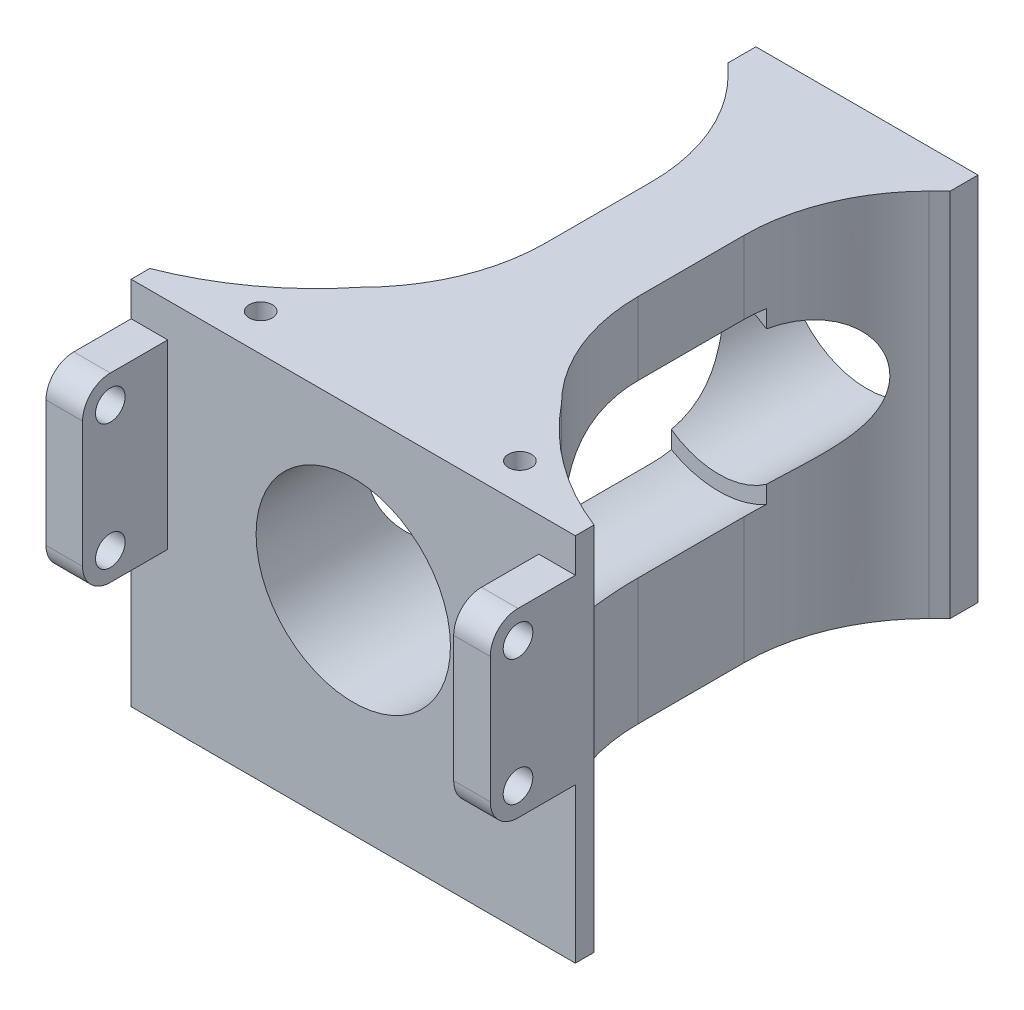
SolidWorks part; units mm, degrees
material "6061 合金"
ref_plane "前视基准面" through (0, 0, 0) normal (0, 0, 1) x (1, 0, 0)
ref_plane "上视基准面" through (0, 0, 0) normal (0, 1, 0) x (1, 0, 0)
ref_plane "右视基准面" through (0, 0, 0) normal (1, 0, 0) x (0, 0, -1)
sketch "草图1" plane through (0, 0, 0) normal (0, 0, 1) x (1, 0, 0)
  line L1 (-24, -15.5) -> (24, -15.5)
  line L2 (-24, -15.5) -> (-24, 15.5)
  line L3 (-24, 15.5) -> (24, 15.5)
  line L4 (24, -15.5) -> (24, 15.5)
  line L5 (-24, -15.5) -> (24, 15.5) construction
  line L6 (-24, 15.5) -> (24, -15.5) construction
  circle A1 centre (0, -0.6) radius 8.9
  point P0 (0, 0)
  dimension "D3" = 17.8
  dimension "D1" = 48
  dimension "D2" = 31
  dimension "D4" = 0.6
extrude "凸台-拉伸1" add sketch "草图1" along normal blind 65
sketch "草图2" plane through (0, 0, 65) normal (0, 0, 1) x (1, 0, 0)
  circle A0 centre (0, -0.6) radius 10.5
  dimension "D1" = 21
  dimension "D2" = 0.6
extrude "切除-拉伸1" cut sketch "草图2" against normal offset from surface (49 mm away) 16 up to face at (0, 0, 0)
sketch "草图4" plane through (0, 15.5, 0) normal (0, 1, 0) x (1, 0, 0)
  line L0 (-24, 9) -> (-10.8579, -4.1421)
  line L1 (-24, -65) -> (-24, 0) construction
  line L2 (-5, -18.2843) -> (-5, -29.7157)
  line L3 (-10.8579, -43.8579) -> (-24, -57) construction
  line L4 (-24, -57) -> (-24, 9) construction
  line L5 (0, 0) -> (0, -65) construction
  line L6 (24, -65) -> (-24, -65) construction
  line L7 (-24, -65) -> (-24, -62) construction
  line L8 (-24, -62) -> (-21, -62) construction
  line L9 (24, 0) -> (-24, 0) construction
  line L10 (10.8579, -43.8579) -> (24, -57) construction
  line L11 (5, -18.2843) -> (5, -29.7157)
  line L12 (24, 9) -> (10.8579, -4.1421)
  line L13 (24, -57) -> (24, 9) construction
  line L14 (35.5, -24) -> (-35.5, -24) construction
  line L15 (9.5, -2.5) -> (-9.5, -2.5) construction
  line L16 (24, -53.4842) -> (24, 9)
  line L17 (-24, -53.4842) -> (-24, 9)
  arc A2 (5, -18.2843) -> (10.8579, -4.1421) centre (25, -18.2843) cw
  arc A3 (10.8579, -43.8579) -> (5, -29.7157) centre (25, -29.7157) cw
  arc A4 (-5, -29.7157) -> (-10.8579, -43.8579) centre (-25, -29.7157) cw
  arc A5 (-10.8579, -4.1421) -> (-5, -18.2843) centre (-25, -18.2843) cw
  circle A6 centre (-35.5, -24) radius 30 construction
  circle A7 centre (35.5, -24) radius 30 construction
  circle A8 centre (9.5, -2.5) radius 1.2 construction
  circle A9 centre (-9.5, -2.5) radius 1.2 construction
  arc A10 (-10.8579, -43.8579) -> (-24, -53.4842) centre (-35.5, -24) cw
  arc A11 (10.8579, -43.8579) -> (24, -53.4842) centre (35.5, -24) ccw
  point P12 (-5, -24)
  point P26 (5, -10)
  point P29 (5, -38)
  point P32 (-5, -38)
  point P35 (-5, -10)
  point P36 (0, -24)
  point P41 (0, -2.5)
  dimension "D3" = 24
  dimension "D7" = 20
  dimension "D4" = 60
  dimension "D11" = 2.4
  dimension "D1" = 3
  dimension "D2" = 3
  dimension "D5" = 10
  dimension "D6" = 10
  dimension "D8" = 71
  dimension "D9" = 2.5
  dimension "D10" = 19
  dimension "D12" = 135
extrude "切除-拉伸3" cut sketch "草图4" against normal through all
sketch "草图12" plane through (0, -15.5, 0) normal (0, -1, 0) x (1, 0, 0)
  line L0 (-5, 18.2843) -> (5, 18.2843)
  line L12 (-15, 0) -> (15, 0)
  line L14 (15, 0) -> (10.8579, 4.1421)
  line L15 (5, 18.2843) -> (5, 29.7157)
  line L17 (24, 53.4842) -> (24, 65)
  line L18 (24, 65) -> (-24, 65)
  line L19 (-24, 65) -> (-24, 53.4842)
  line L21 (-5, 29.7157) -> (-5, 18.2843)
  line L22 (-10.8579, 4.1421) -> (-15, 0)
  line L24 (-15, 0) -> (15, 0) construction
  line L26 (15, 0) -> (10.8579, 4.1421) construction
  line L27 (5, 18.2843) -> (5, 29.7157)
  line L29 (24, 53.4842) -> (24, 65)
  line L30 (24, 65) -> (-24, 65)
  line L31 (-24, 65) -> (-24, 53.4842)
  line L33 (-5, 29.7157) -> (-5, 18.2843)
  line L34 (-10.8579, 4.1421) -> (-15, 0) construction
  arc A4 (5, 18.2843) -> (10.8579, 4.1421) centre (25, 18.2843) ccw
  arc A5 (10.8579, 43.8579) -> (5, 29.7157) centre (25, 29.7157) ccw
  arc A6 (-5, 29.7157) -> (-10.8579, 43.8579) centre (-25, 29.7157) ccw
  arc A7 (-10.8579, 4.1421) -> (-5, 18.2843) centre (-25, 18.2843) ccw
  arc A8 (5, 18.2843) -> (10.8579, 4.1421) centre (25, 18.2843) ccw construction
  arc A9 (10.8579, 43.8579) -> (5, 29.7157) centre (25, 29.7157) ccw
  arc A10 (-5, 29.7157) -> (-10.8579, 43.8579) centre (-25, 29.7157) ccw
  arc A11 (-10.8579, 4.1421) -> (-5, 18.2843) centre (-25, 18.2843) ccw construction
  arc A14 (24, 53.4842) -> (10.8579, 43.8579) centre (35.5, 24) ccw
  arc A15 (24, 53.4842) -> (10.8579, 43.8579) centre (35.5, 24) ccw
  arc A16 (-10.8579, 43.8579) -> (-24, 53.4842) centre (-35.5, 24) ccw
  arc A17 (-10.8579, 43.8579) -> (-24, 53.4842) centre (-35.5, 24) ccw
  dimension "D1" = 0
extrude "凸台-拉伸4" add sketch "草图12" along normal blind 8
sketch "草图11" plane through (0, 15.5, 0) normal (0, 1, 0) x (1, 0, 0)
  line L0 (14, -51.5) -> (-14, -51.5) construction
  line L1 (0, -51.5) -> (0, 0) construction
  circle A0 centre (14, -51.5) radius 1.25
  circle A1 centre (-14, -51.5) radius 1.25
  dimension "D3" = 2.5
  dimension "D1" = 51.5
  dimension "D2" = 28
extrude "切除-拉伸9" cut sketch "草图11" against normal through all
sketch "草图15" plane through (0, 15.5, 0) normal (0, 1, 0) x (1, 0, 0)
  line L0 (24, -65) -> (-24, -65) construction
  line L1 (20.05, -65) -> (-20.05, -65)
  line L2 (20.05, -65) -> (20.05, -55.5)
  line L3 (20.05, -55.5) -> (-20.05, -55.5)
  line L4 (-20.05, -65) -> (-20.05, -55.5)
  line L5 (0, 0) -> (0, -55.5) construction
  circle A0 centre (-14, -51.5) radius 1.25 construction
  dimension "D1" = 40.1
  dimension "D2" = 4
extrude "切除-拉伸11" cut sketch "草图15" against normal through all
sketch "草图17" plane through (24, 0, 0) normal (1, 0, 0) x (0, 0, -1)
  line L0 (-53.4842, -23.5) -> (-65, -23.5) construction
  line L1 (-65, 15.5) -> (-53.4842, 15.5) construction
  line L2 (-61.7, 9.8) -> (-61.7, -3.8) construction
  line L3 (-61.7, 3) -> (-55.5, 3) construction
  line L4 (-55.5, -23.5) -> (-55.5, -6.8)
  line L5 (-55.5, -6.8) -> (-61.7, -6.8)
  line L6 (-64.7, -3.8) -> (-64.7, 9.8)
  line L9 (-64.7, 15.5) -> (-94.5, 15.5)
  line L10 (-94.5, 15.5) -> (-94.5, -23.5)
  line L11 (-94.5, -23.5) -> (-55.5, -23.5)
  line L12 (-55.5, -23.5) -> (-55.5, 15.5) construction
  line L13 (-61.7, 12.8) -> (-55.5, 12.8)
  line L14 (-55.5, 12.8) -> (-55.5, 15.5)
  line L15 (-55.5, 15.5) -> (-64.7, 15.5)
  circle A0 centre (-61.7, 9.8) radius 1.6
  circle A1 centre (-61.7, -3.8) radius 1.6
  arc A3 (-61.7, -6.8) -> (-64.7, -3.8) centre (-61.7, -3.8) cw
  arc A4 (-61.7, 12.8) -> (-64.7, 9.8) centre (-61.7, 9.8) ccw
  dimension "D3" = 3.2
  dimension "D4" = 3
  dimension "D1" = 13.6
  dimension "D2" = 6.2
  dimension "D6" = 12.5
extrude "切除-拉伸13" cut sketch "草图17" against normal through all
sketch "草图19" plane through (0, -15.5, 0) normal (0, -1, 0) x (1, 0, 0)
  line L0 (-10.8579, 4.1421) -> (-15, 0) construction
  line L1 (-15, 0) -> (-12, 0)
  line L2 (-15, 0) -> (-15, 3)
  line L3 (-15, 3) -> (-12, 3)
  line L4 (-12, 0) -> (-12, 3)
  line L5 (15, 0) -> (10.8579, 4.1421) construction
  line L6 (15, 0) -> (12, 0)
  line L7 (15, 0) -> (15, 3)
  line L8 (15, 3) -> (12, 3)
  line L9 (12, 0) -> (12, 3)
  dimension "D1" = 3
extrude "切除-拉伸14" cut sketch "草图19" against normal through all
sketch "草图20" plane through (0, -15.5, 0) normal (0, -1, 0) x (1, 0, 0)
  line L6 (-10.8579, 4.1421) -> (-12, 3)
  line L7 (-12, 3) -> (-12, 0)
  line L8 (-12, 0) -> (12, 0)
  line L9 (12, 0) -> (12, 3)
  line L10 (12, 3) -> (10.8579, 4.1421)
  line L11 (5, 18.2843) -> (-5, 18.2843)
  line L12 (-10.8579, 4.1421) -> (-12, 3)
  line L13 (-12, 3) -> (-12, 0)
  line L14 (-12, 0) -> (12, 0)
  line L15 (12, 0) -> (12, 3)
  line L16 (12, 3) -> (10.8579, 4.1421)
  line L17 (5, 18.2843) -> (-5, 18.2843)
  arc A2 (5, 18.2843) -> (10.8579, 4.1421) centre (25, 18.2843) ccw
  arc A3 (-10.8579, 4.1421) -> (-5, 18.2843) centre (-25, 18.2843) ccw
  arc A4 (5, 18.2843) -> (10.8579, 4.1421) centre (25, 18.2843) ccw
  arc A5 (-10.8579, 4.1421) -> (-5, 18.2843) centre (-25, 18.2843) ccw
  dimension "D1" = 0
extrude "凸台-拉伸5" add sketch "草图20" along normal up to surface (8 mm away) up to face at (0, -23.5, 40.457)
sketch "草图21" plane through (0, 15.5, 0) normal (0, 1, 0) x (1, 0, 0)
  line L10 (12, 0) -> (-12, 0)
  line L11 (-12, 0) -> (-12, -3)
  line L12 (-12, -3) -> (-10.8579, -4.1421)
  line L13 (-5, -18.2843) -> (-5, -29.7157)
  line L14 (-24, -53.4842) -> (-24, -55.5)
  line L15 (-24, -55.5) -> (24, -55.5)
  line L16 (24, -55.5) -> (24, -53.4842)
  line L17 (5, -29.7157) -> (5, -18.2843)
  line L18 (10.8579, -4.1421) -> (12, -3)
  line L19 (12, -3) -> (12, 0)
  line L20 (12, 0) -> (-12, 0)
  line L21 (-12, 0) -> (-12, -3)
  line L22 (-12, -3) -> (-10.8579, -4.1421)
  line L23 (-5, -18.2843) -> (-5, -29.7157)
  line L24 (-24, -53.4842) -> (-24, -55.5)
  line L25 (-24, -55.5) -> (24, -55.5)
  line L26 (24, -55.5) -> (24, -53.4842)
  line L27 (5, -29.7157) -> (5, -18.2843)
  line L28 (10.8579, -4.1421) -> (12, -3)
  line L29 (12, -3) -> (12, 0)
  arc A6 (-5, -18.2843) -> (-10.8579, -4.1421) centre (-25, -18.2843) ccw
  arc A7 (-10.8579, -43.8579) -> (-5, -29.7157) centre (-25, -29.7157) ccw
  arc A8 (-24, -53.4842) -> (-10.8579, -43.8579) centre (-35.5, -24) ccw
  arc A9 (10.8579, -43.8579) -> (24, -53.4842) centre (35.5, -24) ccw
  arc A10 (5, -29.7157) -> (10.8579, -43.8579) centre (25, -29.7157) ccw
  arc A11 (10.8579, -4.1421) -> (5, -18.2843) centre (25, -18.2843) ccw
  arc A12 (-5, -18.2843) -> (-10.8579, -4.1421) centre (-25, -18.2843) ccw
  arc A13 (-10.8579, -43.8579) -> (-5, -29.7157) centre (-25, -29.7157) ccw
  arc A14 (-24, -53.4842) -> (-10.8579, -43.8579) centre (-35.5, -24) ccw
  arc A15 (10.8579, -43.8579) -> (24, -53.4842) centre (35.5, -24) ccw
  arc A16 (5, -29.7157) -> (10.8579, -43.8579) centre (25, -29.7157) ccw
  arc A17 (10.8579, -4.1421) -> (5, -18.2843) centre (25, -18.2843) ccw
  dimension "D1" = 0
extrude "凸台-拉伸6" add sketch "草图21" along normal blind 1
sketch "草图22" plane through (0, 15.5, 0) normal (0, -1, 0) x (1, 0, 0)
  circle A1 centre (-14, 51.5) radius 1.25
  circle A2 centre (-14, 51.5) radius 1.25
  circle A3 centre (14, 51.5) radius 1.25
  circle A4 centre (14, 51.5) radius 1.25
  dimension "D1" = 0
  dimension "D2" = 0
extrude "切除-拉伸15" cut sketch "草图22" against normal blind 10
sketch "草图23" plane through (0, -23.5, 0) normal (0, -1, 0) x (1, 0, 0)
  line L0 (-12, 0) -> (12, 0) construction
  circle A0 centre (0, 6) radius 1.25
  dimension "D1" = 2.5
  dimension "D2" = 6
extrude "切除-拉伸16" cut sketch "草图23" against normal blind 7
